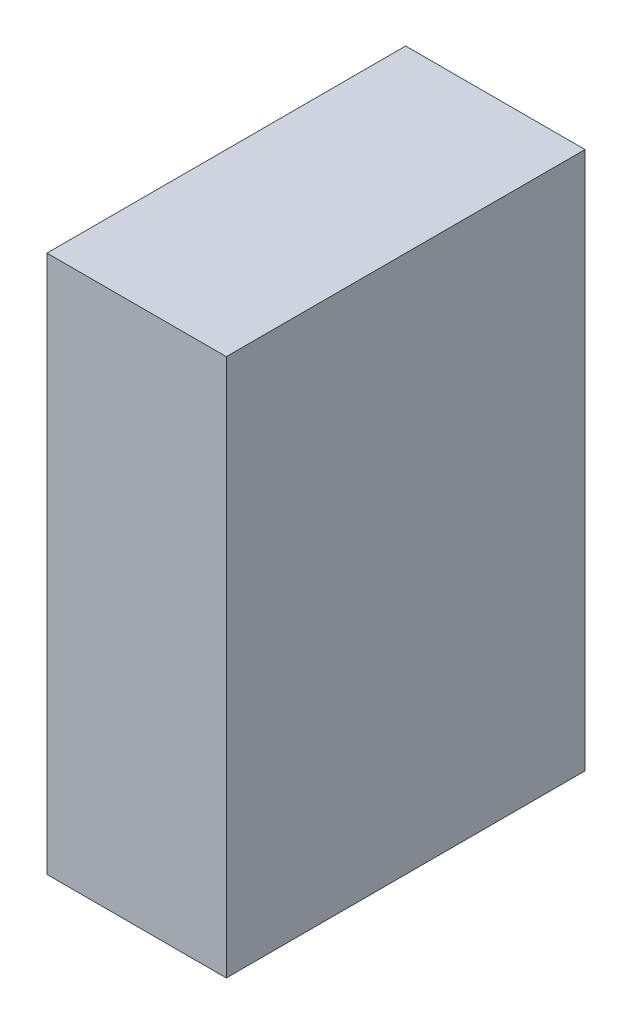
SolidWorks part; units mm, degrees
other "Markup1"
sketch "Sketch2" plane through (12.7, 25.4, 0) normal (0.4, 0.515, 0.7581) x (0.8844, 0, -0.4667)
ref_plane "Front Plane" through (0, 0, 0) normal (0, 0, 1) x (1, 0, 0)
ref_plane "Top Plane" through (0, 0, 0) normal (0, 1, 0) x (1, 0, 0)
ref_plane "Right Plane" through (0, 0, 0) normal (1, 0, 0) x (0, 0, -1)
sketch "Sketch1" plane through (0, 0, 0) normal (0, 1, 0) x (1, 0, 0)
  line L1 (0, 0) -> (12.7, 0)
  line L2 (0, 0) -> (0, 25.4)
  line L3 (0, 25.4) -> (12.7, 25.4)
  line L4 (12.7, 0) -> (12.7, 25.4)
  dimension "D1" = 12.7
  dimension "D2" = 25.4
extrude "Boss-Extrude1" add sketch "Sketch1" along normal blind 38.1
